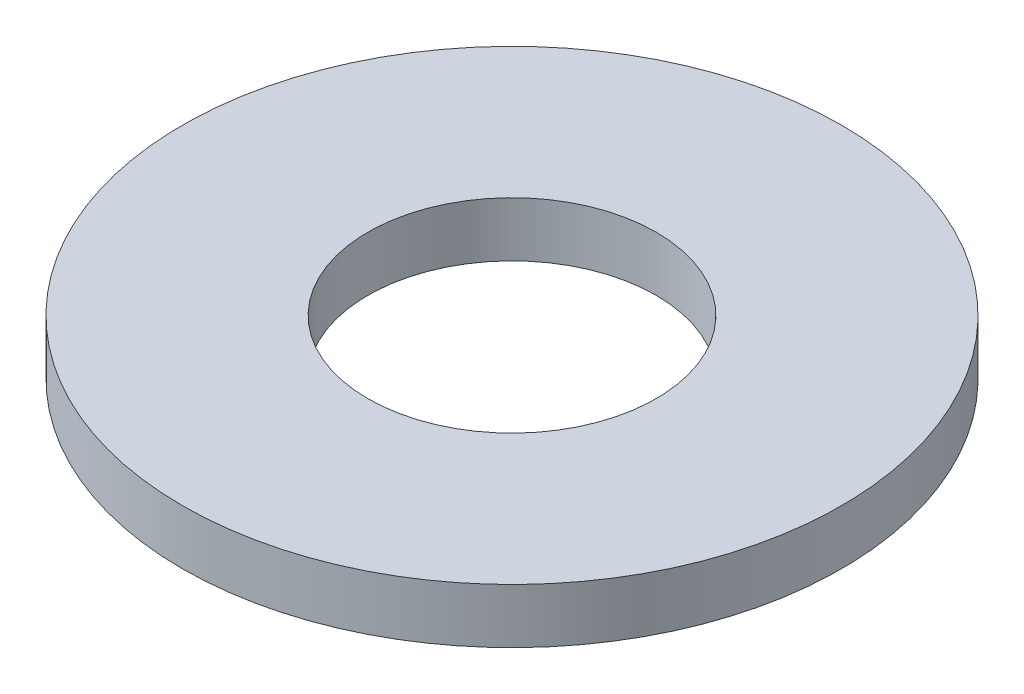
SolidWorks part; units mm, degrees
ref_plane "Front Plane" through (0, 0, 0) normal (0, 0, 1) x (1, 0, 0)
ref_plane "Top Plane" through (0, 0, 0) normal (0, 1, 0) x (1, 0, 0)
ref_plane "Right Plane" through (0, 0, 0) normal (1, 0, 0) x (0, 0, -1)
sketch "Sketch1" plane through (0, 0, 0) normal (0, 1, 0) x (1, 0, 0)
  circle A0 centre (0, 0) radius 12.7
  circle A2 centre (0, 0) radius 5.5562
  dimension "D1" = 25.4
  dimension "D2" = 11.1125
extrude "Boss-Extrude1" add sketch "Sketch1" along normal blind 2.1082
